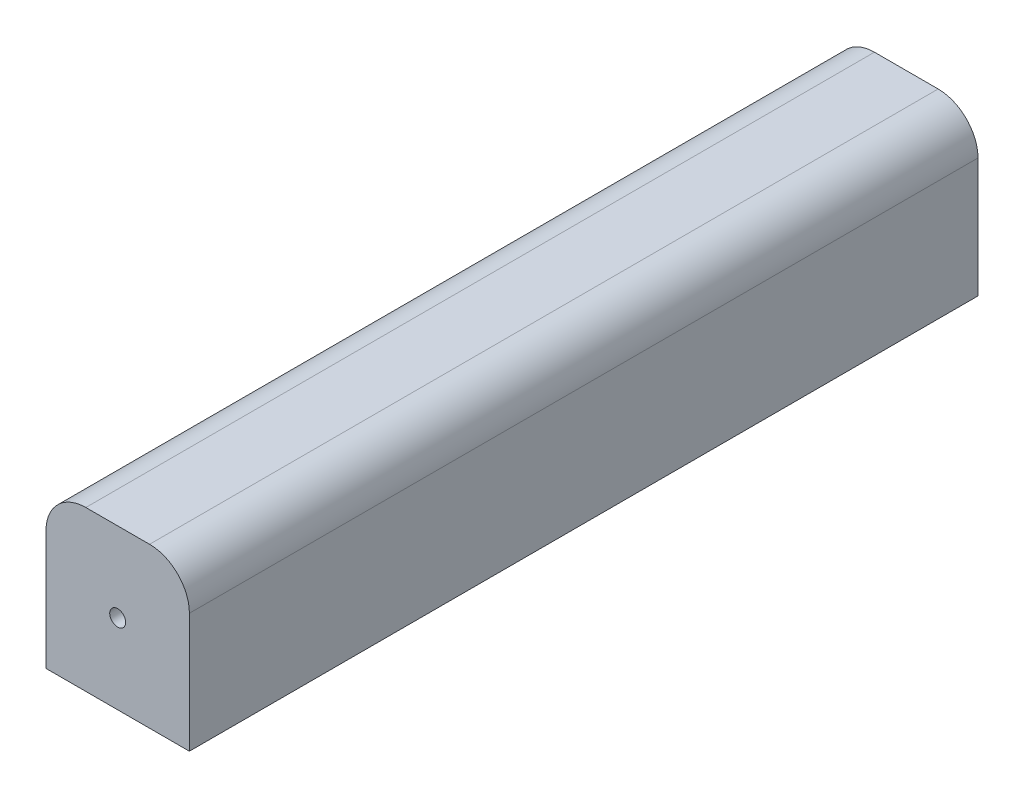
SolidWorks part; units mm, degrees
ref_plane "前视基准面" through (0, 0, 0) normal (0, 0, 1) x (1, 0, 0)
ref_plane "上视基准面" through (0, 0, 0) normal (0, 1, 0) x (1, 0, 0)
ref_plane "右视基准面" through (0, 0, 0) normal (1, 0, 0) x (0, 0, -1)
sketch "草图1" plane through (0, 0, 0) normal (0, 0, 1) x (1, 0, 0)
  line L1 (-4, 10) -> (4, 10)
  line L2 (-9, 5) -> (-9, -10)
  line L3 (-9, -10) -> (9, -10)
  line L4 (9, 5) -> (9, -10)
  line L5 (-9, 10) -> (9, -10) construction
  line L6 (-9, -10) -> (9, 10) construction
  arc A0 (4, 10) -> (9, 5) centre (4, 5) cw
  arc A1 (-4, 10) -> (-9, 5) centre (-4, 5) ccw
  point P0 (0, 0)
  dimension "D1" = 18
  dimension "D3" = 5
  dimension "D2" = 20
extrude "凸台-拉伸1" add sketch "草图1" along normal blind 99
sketch "草图2" plane through (0, 0, 99) normal (0, 0, 1) x (1, 0, 0)
  circle A0 centre (0, 0) radius 1
extrude "切除-拉伸1" cut sketch "草图2" against normal blind 5
sketch "草图3" plane through (0, 0, 0) normal (0, 0, -1) x (-1, 0, 0)
  circle A0 centre (0, 0) radius 1
extrude "切除-拉伸2" cut sketch "草图3" against normal blind 5
